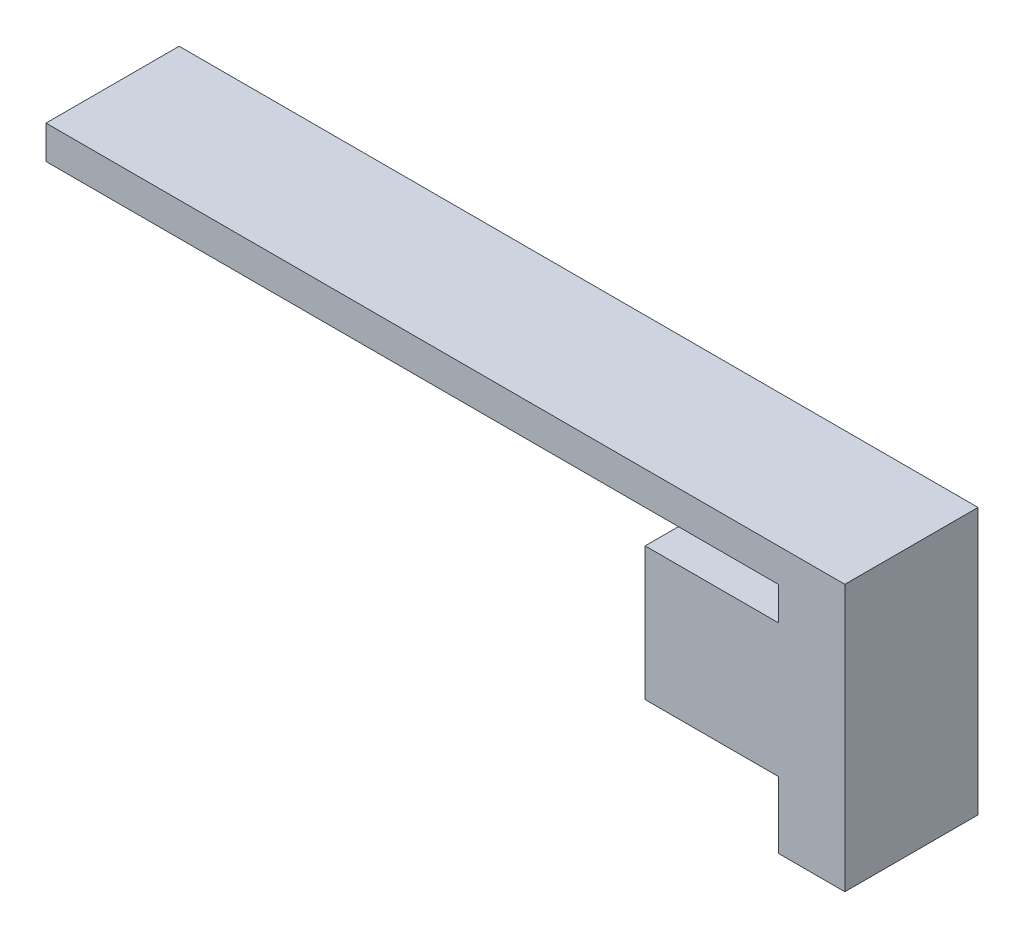
SolidWorks part; units mm, degrees
ref_plane "前视基准面" through (0, 0, 0) normal (0, 0, 1) x (1, 0, 0)
ref_plane "上视基准面" through (0, 0, 0) normal (0, 1, 0) x (1, 0, 0)
ref_plane "右视基准面" through (0, 0, 0) normal (1, 0, 0) x (0, 0, -1)
sketch "草图1" plane through (0, 0, 0) normal (0, 1, 0) x (1, 0, 0)
  line L1 (-30, -5) -> (30, -5)
  line L2 (-30, -5) -> (-30, 5)
  line L3 (-30, 5) -> (30, 5)
  line L4 (30, -5) -> (30, 5)
  line L5 (-30, -5) -> (30, 5) construction
  line L6 (-30, 5) -> (30, -5) construction
  point P0 (0, 0)
  dimension "D1" = 60
  dimension "D2" = 10
extrude "凸台-拉伸1" add sketch "草图1" along normal blind 2.5
sketch "草图2" plane through (0, 0, 0) normal (1, 0, 0) x (0, 0, -1)
  line L1 (-5, 2.5) -> (5, 2.5)
  line L2 (-5, 2.5) -> (-5, -17.5)
  line L3 (-5, -17.5) -> (5, -17.5)
  line L4 (5, 2.5) -> (5, -17.5)
  dimension "D1" = 10
  dimension "D2" = 20
extrude "凸台-拉伸2" add sketch "草图2" along normal blind 5 from offset 25
sketch "草图5" plane through (25, 0, 0) normal (-1, 0, 0) x (0, 0, 1)
  line L0 (-5, -17.5) -> (-5, 0) construction
  line L1 (-5, -2.5) -> (5, -2.5)
  line L2 (-5, -2.5) -> (-5, -12.5)
  line L3 (-5, -12.5) -> (5, -12.5)
  line L4 (5, -2.5) -> (5, -12.5)
  line L5 (5, 0) -> (5, -17.5) construction
extrude "凸台-拉伸3" add sketch "草图5" along normal blind 10
